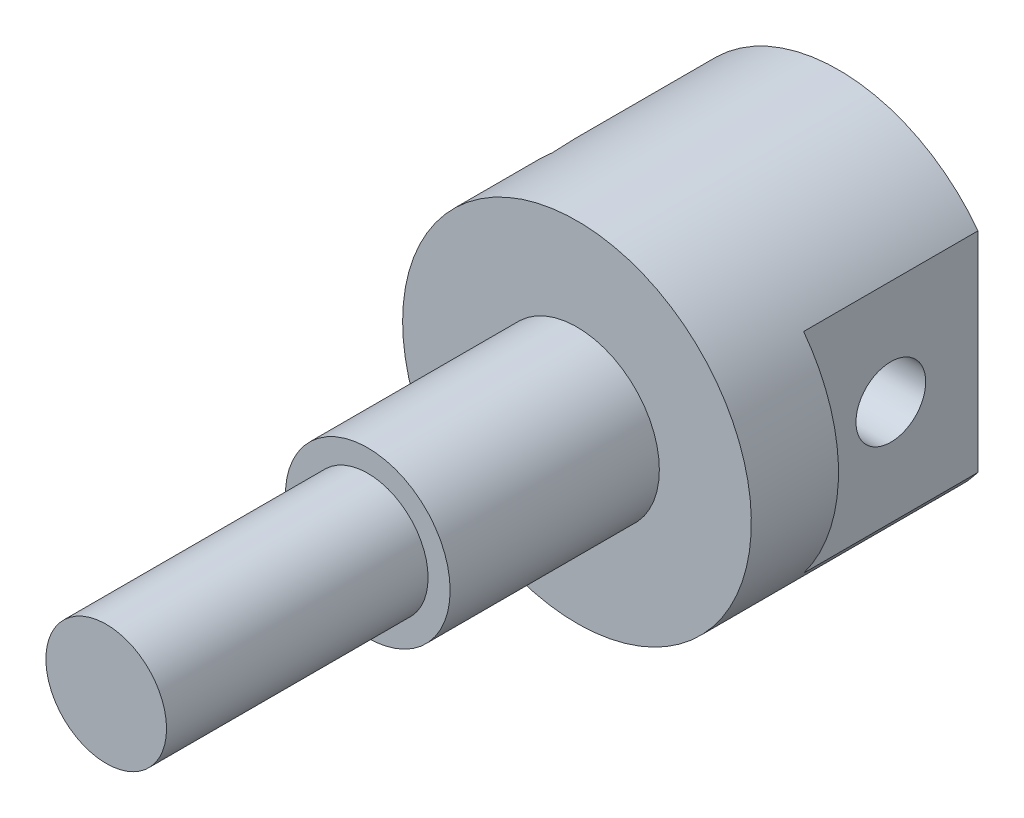
SolidWorks part; units mm, degrees
material "ABS"
ref_plane "Front Plane" through (0, 0, 0) normal (0, 0, 1) x (1, 0, 0)
ref_plane "Top Plane" through (0, 0, 0) normal (0, 1, 0) x (1, 0, 0)
ref_plane "Right Plane" through (0, 0, 0) normal (1, 0, 0) x (0, 0, -1)
sketch "Sketch1" plane through (0, 0, 0) normal (0, 0, 1) x (1, 0, 0)
  circle A0 centre (0, 0) radius 4.725
  dimension "D1" = 9.45
extrude "Boss-Extrude1" add sketch "Sketch1" against normal blind 12
sketch "Sketch2" plane through (0, 0, 0) normal (0, 0, 1) x (1, 0, 0)
  circle A0 centre (0, 0) radius 3.46
  dimension "D1" = 6.92
extrude "Boss-Extrude2" add sketch "Sketch2" along normal blind 15
sketch "Sketch5" plane through (0, 0, -12) normal (0, 0, -1) x (-1, 0, 0)
  circle A0 centre (0, 0) radius 10
  dimension "D1" = 20
extrude "Boss-Extrude3" add sketch "Sketch5" along normal blind 15
sketch "Sketch3" plane through (0, 0, 0) normal (1, 0, 0) x (0, 0, -1)
  line L0 (27, -5) -> (27, 5)
  line L2 (27, 0) -> (17, 0) construction
  line L3 (17, -7.6795) -> (17, 7.6795)
  line L4 (17, 7.6795) -> (27, 5)
  line L5 (17, -7.6795) -> (27, -5)
  line L9 (27, -10) -> (27, 10) construction
  point P3 (0, 0)
  point P4 (0, 0)
  point P5 (18.6, 4.911)
  point P7 (25, 1.6384)
  point P8 (20.933, 3.2073)
  point P11 (17, 0)
  point P12 (23.7636, 2.1721)
  point P15 (21.7475, -2.725)
  point P16 (25, -1.6532)
  point P18 (25, 2.7742)
  point P21 (22, -2)
  point P22 (21.1975, -11.7912)
  dimension "D1" = 75
  dimension "D2" = 10
  dimension "D3" = 10
extrude "Cut-Extrude1" cut sketch "Sketch3" against normal blind 15 and the other way blind 5
sketch "Sketch4" plane through (0, 0, -27) normal (0, 0, -1) x (-1, 0, 0)
  line L0 (-10, 0) -> (0, 0) construction
  line L1 (-10, 6) -> (-8, 6)
  line L2 (-10, 6) -> (-10, -6)
  line L3 (-10, -6) -> (-8, -6)
  line L4 (-8, 6) -> (-8, -6)
  arc A1 (8.6603, 5) -> (8.6603, -5) centre (0, 0) ccw construction
  point P6 (0, 0)
  point P11 (0, 0)
  point P13 (-8, 0)
  dimension "D1" = 2
extrude "Cut-Extrude2" cut sketch "Sketch4" against normal up to surface (10 mm away) up to face at (-1.6013, 0, -17)
sketch "Sketch6" plane through (8, 0, 0) normal (1, 0, 0) x (0, 0, -1)
  line L0 (17, 6) -> (27, -6) construction
  circle A0 centre (22, 0) radius 2
  dimension "D1" = 4
extrude "Cut-Extrude3" cut sketch "Sketch6" against normal up to next
